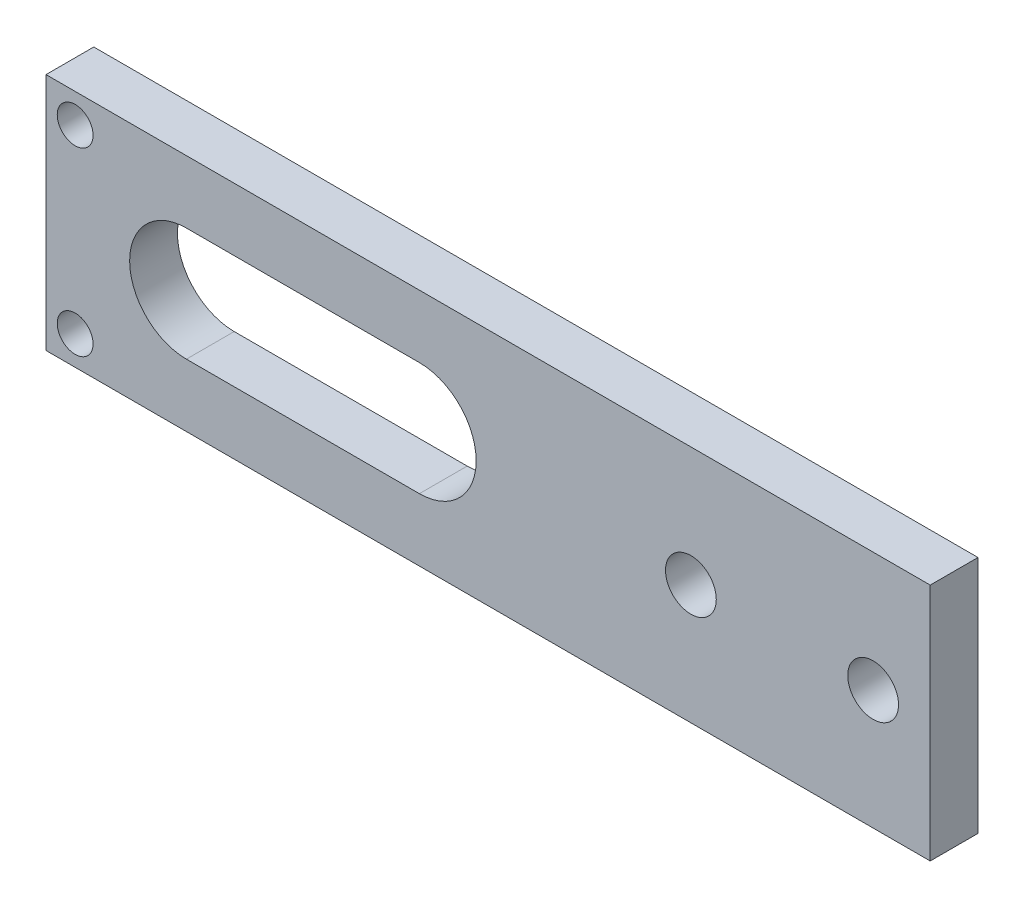
SolidWorks part; units mm, degrees
ref_plane "Front Plane" through (0, 0, 0) normal (0, 0, 1) x (1, 0, 0)
ref_plane "Top Plane" through (0, 0, 0) normal (0, 1, 0) x (1, 0, 0)
ref_plane "Right Plane" through (0, 0, 0) normal (1, 0, 0) x (0, 0, -1)
sketch "Sketch1" plane through (0, 0, 0) normal (0, 0, 1) x (1, 0, 0)
  line L0 (-25.25, 0) -> (-5.75, 0) construction
  line L1 (-37, 10) -> (37, 10)
  line L2 (-37, 10) -> (-37, -10)
  line L3 (-37, -10) -> (37, -10)
  line L4 (37, 10) -> (37, -10)
  line L5 (-37, 10) -> (37, -10) construction
  line L6 (-37, -10) -> (37, 10) construction
  line L7 (-25.25, 4.75) -> (-5.75, 4.75)
  line L8 (-25.25, -4.75) -> (-5.75, -4.75)
  line L9 (40.7, 0) -> (-40.7, 0) construction
  circle A0 centre (32.2219, 0) radius 2.125
  circle A1 centre (16.9719, 0) radius 2.125
  arc A2 (-25.25, 4.75) -> (-25.25, -4.75) centre (-25.25, 0) ccw
  arc A3 (-5.75, -4.75) -> (-5.75, 4.75) centre (-5.75, 0) ccw
  circle A4 centre (-34.5593, -7.5593) radius 2.4407 construction
  circle A5 centre (-34.5593, -7.5593) radius 1.5
  circle A6 centre (-34.5593, 7.5593) radius 1.5
  point P1 (0, 0)
  point P12 (-15.5, 0)
  point P17 (-30, 0)
  dimension "D3" = 4.25
  dimension "D5" = 4.75
  dimension "D1" = 74
  dimension "D2" = 20
  dimension "D6" = 19.5
  dimension "D7" = 7
  dimension "D4" = 2
extrude "Boss-Extrude1" add sketch "Sketch1" along normal blind 4
